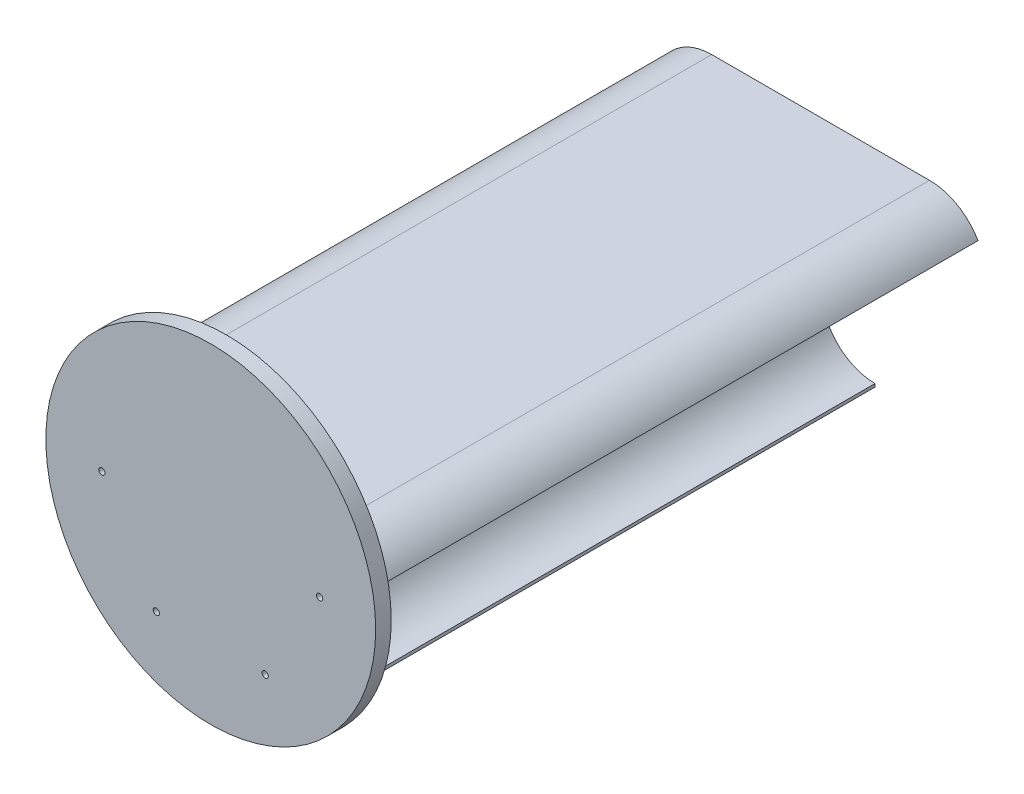
SolidWorks part; units mm, degrees
ref_plane "Plan de face" through (0, 0, 0) normal (0, 0, 1) x (1, 0, 0)
ref_plane "Plan de dessus" through (0, 0, 0) normal (0, 1, 0) x (1, 0, 0)
ref_plane "Plan de droite" through (0, 0, 0) normal (1, 0, 0) x (0, 0, -1)
sketch "Esquisse1" plane through (0, 0, 0) normal (0, 0, 1) x (1, 0, 0)
  line L0 (-35, 0) -> (35, 0) construction
  line L2 (0, 0) -> (0, -53.5) construction
  line L4 (-31.4635, 18.3063) -> (31.5363, 18.1806) construction
  line L5 (-31.4635, 18.3063) -> (-31.4137, 43.3063) construction
  line L6 (-31.4137, 43.3063) -> (31.5862, 43.1806) construction
  line L7 (31.5363, 18.1806) -> (31.5862, 43.1806) construction
  line L8 (-49.7224, 8.5) -> (-35, 0) construction
  line L9 (-35, 0) -> (-49.7224, -8.5) construction
  line L12 (-17.5, -48.3109) -> (-17.5, -47.3109)
  line L17 (-34.6353, -19.9967) -> (0, 0) construction
  line L22 (-49.7224, 8.5) -> (-50.5885, 9)
  line L23 (-49.7224, -8.5) -> (-50.5885, -9)
  line L24 (49.7224, 8.5) -> (50.5885, 9)
  line L25 (-32.2224, -38.8109) -> (-33.0885, -39.3109)
  line L26 (49.7224, -8.5) -> (50.5885, -9)
  line L27 (32.2224, -38.8109) -> (33.0885, -39.3109)
  line L28 (17.5, -48.3109) -> (17.5, -47.3109)
  line L29 (35, 18) -> (-35, 18)
  circle A0 centre (0, 0) radius 17.5 construction
  circle A1 centre (35, 0) radius 17.5 construction
  circle A2 centre (-35, 0) radius 17.5 construction
  circle A3 centre (-17.5, -30.3109) radius 17.5 construction
  circle A4 centre (17.5, -30.3109) radius 17.5 construction
  circle A6 centre (0, 0) radius 53.5 construction
  circle A7 centre (0, 0) radius 17 construction
  circle A8 centre (35, 0) radius 17 construction
  circle A11 centre (17.5, -30.3109) radius 17 construction
  arc A12 (-49.7224, 8.5) -> (-49.7224, -8.5) centre (-35, 0) cw
  circle A24 centre (-35, 0) radius 18 construction
  arc A25 (-50.5885, -9) -> (-29.8986, -17.262) centre (-35, 0) ccw
  arc A26 (-17.5, -47.3109) -> (-32.2224, -38.8109) centre (-17.5, -30.3109) ccw
  arc A27 (-33.0885, -39.3109) -> (-29.8986, -17.262) centre (-17.5, -30.3109) cw
  arc A28 (50.5885, 9) -> (35, 18) centre (35, 0) ccw
  arc A29 (-17.5, -48.3109) -> (0, -34.524) centre (-17.5, -30.3109) ccw
  arc A30 (-50.5885, 9) -> (-35, 18) centre (-35, 0) cw
  arc A31 (49.7224, 8.5) -> (49.7224, -8.5) centre (35, 0) ccw
  arc A32 (50.5885, -9) -> (29.8986, -17.262) centre (35, 0) cw
  arc A33 (33.0885, -39.3109) -> (29.8986, -17.262) centre (17.5, -30.3109) ccw
  arc A34 (17.5, -47.3109) -> (32.2224, -38.8109) centre (17.5, -30.3109) cw
  arc A35 (17.5, -48.3109) -> (0, -34.524) centre (17.5, -30.3109) cw
  point P48 (0, 0)
  point P61 (0, 0)
  dimension "D1" = 35
  dimension "D2" = 1
  dimension "D5" = 17
  dimension "D6" = 17
  dimension "D7" = 60
  dimension "D8" = 35
  dimension "D9" = 20
  dimension "D10" = 1
  dimension "D13" = 107
  dimension "D3" = 63
  dimension "D4" = 25
extrude "Boss.-Extru.1" add sketch "Esquisse1" along normal blind 191
sketch "Esquisse4" plane through (0, 0, 191) normal (0, 0, 1) x (1, 0, 0)
  line L0 (0, 0) -> (29.8986, -17.262) construction
  line L1 (0, 0) -> (-29.8986, -17.262) construction
  line L2 (0, 0) -> (0, -34.524) construction
  line L3 (11.2597, -14.4977) -> (18.1852, -2.5023)
  line L4 (-33.0885, -39.3109) -> (-32.2224, -38.8109)
  line L5 (18.1852, -2.5023) -> (49.7224, -8.5)
  line L6 (49.7224, -8.5) -> (50.5885, -9)
  line L7 (50.5885, -9) -> (33.0885, -39.3109)
  line L8 (33.0885, -39.3109) -> (32.2224, -38.8109)
  line L10 (32.2224, -38.8109) -> (11.2597, -14.4977)
  line L11 (-50.5885, -9) -> (-33.0885, -39.3109)
  line L12 (-49.7224, -8.5) -> (-50.5885, -9)
  line L13 (-18.1852, -2.5023) -> (-49.7224, -8.5)
  line L14 (-11.2597, -14.4977) -> (-18.1852, -2.5023)
  line L15 (-32.2224, -38.8109) -> (-11.2597, -14.4977)
  line L16 (-49.7224, -8.5) -> (-50.5885, -9) construction
  arc A2 (33.0885, -39.3109) -> (29.8986, -17.262) centre (17.5, -30.3109) ccw construction
  arc A3 (49.7224, 8.5) -> (49.7224, -8.5) centre (35, 0) ccw construction
  arc A4 (32.2224, -38.8109) -> (17.5, -47.3109) centre (17.5, -30.3109) ccw construction
  point P10 (0, 0)
  point P11 (18.1818, -2.4794)
  point P12 (11.1212, -14.553)
  point P19 (0, 0)
  point P26 (33.1012, -39.2888)
  point P31 (47.9458, -10.2419)
  point P32 (0, 0)
  point P33 (50.289, -1.4967)
  point P34 (48.3596, -8.6976)
  point P36 (0, 0)
  point P37 (0, 0)
  point P40 (32.2224, -38.8109)
  point P42 (0, 0)
  point P43 (0, 0)
  point P44 (50.5885, -9)
  point P46 (49.7069, -8.5268)
  point P50 (0, 0)
  point P51 (0, 0)
  point P52 (-49.7224, -8.5)
  point P55 (-33.0885, -39.3109)
  point P57 (0, 0)
  point P58 (0, -34.524)
  point P60 (0, 0)
  point P61 (0, 0)
  point P62 (0, 0)
  point P63 (29.8986, -17.262)
  point P65 (-29.8986, -17.262)
  dimension "D1" = 17
extrude "Enlèv. mat.-Extru.1" cut sketch "Esquisse4" against normal through all
sketch "Esquisse2" plane through (0, 0, 191) normal (0, 0, 1) x (1, 0, 0)
  line L0 (17.5, -30.3109) -> (35, 0) construction
  line L1 (34.2007, 12.8745) -> (49.4683, 4.0598) construction
  line L2 (49.4683, 4.0598) -> (21.2183, -44.8707) construction
  line L3 (21.2183, -44.8707) -> (5.9507, -36.0559) construction
  line L4 (5.9507, -36.0559) -> (34.2007, 12.8745) construction
  line L5 (0, 0) -> (26.25, -15.1554) construction
  line L6 (41.674, 8.5598) -> (35.6119, 12.0598)
  line L7 (35.6119, 12.0598) -> (36.6119, 13.7918)
  line L8 (36.6119, 13.7918) -> (42.674, 10.2918)
  line L9 (42.674, 10.2918) -> (41.674, 8.5598)
  line L10 (7.3619, -36.8707) -> (6.3619, -38.6027)
  line L11 (13.424, -40.3707) -> (7.3619, -36.8707)
  line L12 (12.424, -42.1027) -> (13.424, -40.3707)
  line L13 (6.3619, -38.6027) -> (12.424, -42.1027)
  line L14 (0, 0) -> (0, -53) construction
  line L15 (-35.6119, 12.0598) -> (-36.6119, 13.7918)
  line L16 (-41.674, 8.5598) -> (-35.6119, 12.0598)
  line L17 (-42.674, 10.2918) -> (-41.674, 8.5598)
  line L18 (-36.6119, 13.7918) -> (-42.674, 10.2918)
  line L19 (-7.3619, -36.8707) -> (-6.3619, -38.6027)
  line L20 (-13.424, -40.3707) -> (-7.3619, -36.8707)
  line L21 (-12.424, -42.1027) -> (-13.424, -40.3707)
  line L22 (-6.3619, -38.6027) -> (-12.424, -42.1027)
  circle A0 centre (0, 0) radius 53
  circle A1 centre (-35, 0) radius 1
  circle A2 centre (-17.5, -30.3109) radius 1
  circle A3 centre (17.5, -30.3109) radius 1
  circle A4 centre (35, 0) radius 1
  arc A10 (-18.1852, -2.5023) -> (-49.7224, 8.5) centre (-35, 0) ccw construction
  arc A11 (11.2597, -14.4977) -> (17.5, -47.3109) centre (17.5, -30.3109) ccw construction
  arc A12 (49.7224, 8.5) -> (18.1852, -2.5023) centre (35, 0) ccw construction
  arc A13 (-17.5, -47.3109) -> (-11.2597, -14.4977) centre (-17.5, -30.3109) ccw construction
  dimension "D1" = 106
  dimension "D3" = 2
  dimension "D8" = 2
  dimension "D4" = 56.5
  dimension "D5" = 9
  dimension "D6" = 10.5
  dimension "D7" = 7
extrude "Boss.-Extru.2" add sketch "Esquisse2" along normal blind 5
sketch "Esquisse5" plane through (21.4869, -12.4054, 0) normal (0.866, -0.5, 0) x (0, 0, -1)
  line L0 (-196, -28.25) -> (-190.4, -28.25)
  line L1 (-196, -28.25) -> (-188.4, -28.25) construction
  line L2 (-196, -28.25) -> (-196, -30.25)
  line L3 (-196, -30.25) -> (-188.4, -30.25)
  line L4 (-188.4, -28.25) -> (-188.4, -30.25)
  line L5 (-190.4, -28.25) -> (-190.4, -26.25)
  line L6 (-190.4, -26.25) -> (-188.4, -26.25)
  line L7 (-188.4, -26.25) -> (-188.4, -28.25)
  line L8 (-191, 0) -> (-196, 0) construction
  line L9 (-191, 6.9255) -> (-191, -6.9255) construction
  line L10 (-196, 53) -> (-196, -53) construction
  line L11 (-190.4, 26.25) -> (-188.4, 26.25)
  line L12 (-190.4, 28.25) -> (-190.4, 26.25)
  line L13 (-196, 28.25) -> (-190.4, 28.25)
  line L14 (-196, 28.25) -> (-196, 30.25)
  line L15 (-196, 30.25) -> (-188.4, 30.25)
  line L16 (-188.4, 28.25) -> (-188.4, 30.25)
  line L17 (-188.4, 26.25) -> (-188.4, 28.25)
  line L20 (-191, -53) -> (-191, 53) construction
  point P21 (-196, -30.25)
  dimension "D1" = 2
  dimension "D2" = 2
  dimension "D3" = 0.6
extrude "Boss.-Extru.3" add sketch "Esquisse5" along normal up to vertex (7 mm away)
sketch "Esquisse6" plane through (-21.4869, -12.4054, 0) normal (-0.866, -0.5, 0) x (0, 0, 1)
  line L0 (196, -28.25) -> (190.4, -28.25)
  line L1 (196, -28.25) -> (188.4, -28.25) construction
  line L2 (196, -28.25) -> (196, -30.25)
  line L3 (196, -30.25) -> (188.4, -30.25)
  line L4 (188.4, -28.25) -> (188.4, -30.25)
  line L5 (190.4, -28.25) -> (190.4, -26.25)
  line L6 (190.4, -26.25) -> (188.4, -26.25)
  line L7 (188.4, -26.25) -> (188.4, -28.25)
  line L8 (191, 0) -> (189.6636, 0) construction
  line L9 (190.4, 26.25) -> (188.4, 26.25)
  line L10 (190.4, 28.25) -> (190.4, 26.25)
  line L11 (196, 28.25) -> (190.4, 28.25)
  line L12 (196, 28.25) -> (196, 30.25)
  line L13 (196, 30.25) -> (188.4, 30.25)
  line L14 (188.4, 28.25) -> (188.4, 30.25)
  line L15 (188.4, 26.25) -> (188.4, 28.25)
  line L16 (191, 34.5) -> (191, 6.9255) construction
  line L17 (191, 53) -> (191, -53) construction
  point P17 (0, 0)
  point P18 (187.0757, 24.0298)
  point P19 (0, 0)
  point P20 (174.1534, 5.9111)
  point P21 (176.9035, -3.7145)
  point P22 (196, 30.25)
  point P24 (196, 24.4343)
  point P28 (191, 0)
  dimension "D1" = 2
  dimension "D2" = 0.6
  dimension "D3" = 2
extrude "Boss.-Extru.4" add sketch "Esquisse6" along normal up to vertex (7 mm away)
